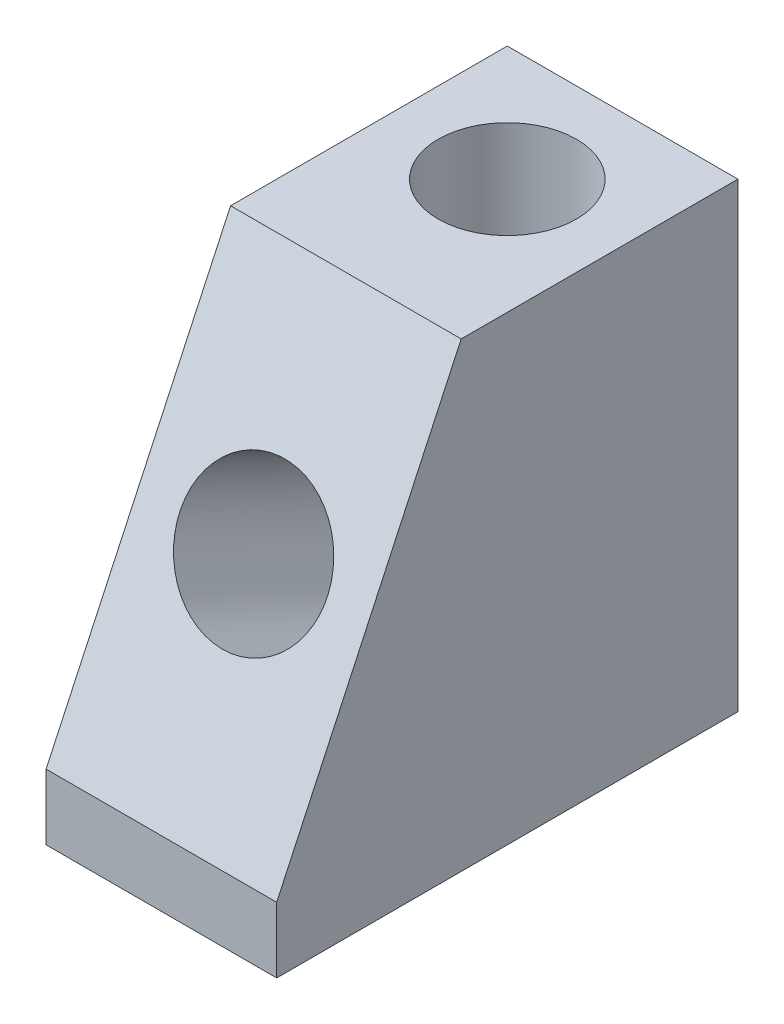
SolidWorks part; units mm, degrees
ref_plane "前视基准面" through (0, 0, 0) normal (0, 0, 1) x (1, 0, 0)
ref_plane "上视基准面" through (0, 0, 0) normal (0, 1, 0) x (1, 0, 0)
ref_plane "右视基准面" through (0, 0, 0) normal (1, 0, 0) x (0, 0, -1)
other "Configuration Table"
sketch "草图1" plane through (0, 0, 0) normal (0, 1, 0) x (1, 0, 0)
  line L1 (0, 0) -> (5, 0)
  line L2 (0, 0) -> (0, 10)
  line L3 (0, 10) -> (5, 10)
  line L4 (5, 0) -> (5, 10)
  circle A0 centre (2.5, 7.5) radius 1.5
  dimension "D3" = 3
  dimension "D1" = 5
  dimension "D2" = 10
  dimension "D4" = 7.5
  dimension "D5" = 2.5
extrude "凸台-拉伸1" add sketch "草图1" along normal blind 10
sketch "草图2" plane through (5, 0, 0) normal (1, 0, 0) x (0, 0, -1)
  line L0 (0, 1.422) -> (4, 10)
  line L1 (0, 10) -> (0, 0) construction
  line L2 (0, 10) -> (10, 10) construction
  line L3 (0, 1.422) -> (0, 10)
  line L4 (0, 10) -> (4, 10)
  dimension "D1" = 65
  dimension "D2" = 4
extrude "切除-拉伸1" cut sketch "草图2" against normal blind 5
sketch "草图3" plane through (0, 0.254, 0.5446) normal (0, 0.4226, 0.9063) x (1, 0, 0)
  line L0 (5, 1.2887) -> (0, 10.7536) construction
  line L1 (0, 10.7536) -> (0, 1.2887)
  line L2 (0, 1.2887) -> (5, 10.7536) construction
  circle A0 centre (2.5, 6.0211) radius 1.6
  dimension "D1" = 3.2
extrude "切除-拉伸2" cut sketch "草图3" against normal through all contours A0
